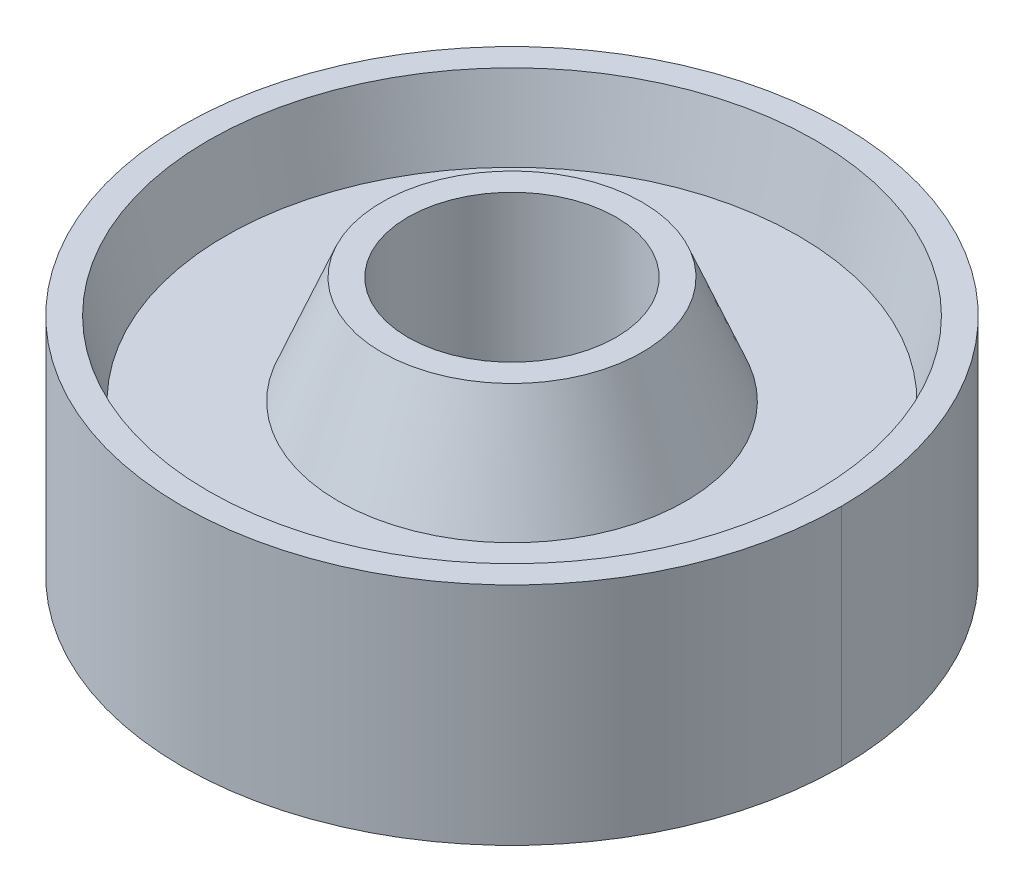
SolidWorks part; units mm, degrees
material "1.6657 (14NiCrMo13-4)"
ref_plane "Alzado" through (0, 0, 0) normal (0, 0, 1) x (1, 0, 0)
ref_plane "Planta" through (0, 0, 0) normal (0, 1, 0) x (1, 0, 0)
ref_plane "Vista lateral" through (0, 0, 0) normal (1, 0, 0) x (0, 0, -1)
sketch "Croquis1" plane through (0, 0, 0) normal (0, 0, 1) x (1, 0, 0)
  line L0 (7.7309, 46.3143) -> (7.7309, 12.6287)
  line L1 (7.7309, 46.3143) -> (22.7309, 46.3143)
  line L2 (22.7309, 46.3143) -> (27.7309, 33.9537)
  line L3 (27.7309, 33.9537) -> (40.7309, 33.9537)
  line L4 (40.7309, 33.9537) -> (42.7309, 42.4715)
  line L5 (42.7309, 42.4715) -> (45.7309, 42.4715)
  line L7 (45.7309, 16.4715) -> (45.7309, 42.4715)
  line L8 (7.7309, 12.6287) -> (22.7309, 12.6287)
  line L9 (22.7309, 12.6287) -> (27.7309, 24.9893)
  line L10 (27.7309, 24.9893) -> (40.7309, 24.9893)
  line L11 (40.7309, 24.9893) -> (42.7309, 16.4715)
  line L12 (7.7309, 46.3143) -> (7.7309, 32.6772) construction
  line L13 (42.7309, 16.4715) -> (45.7309, 16.4715)
  dimension "D2" = 33
  dimension "D3" = 35
  dimension "D4" = 15
  dimension "D5" = 38
  dimension "D6" = 20
revolve "Revolución1" add sketch "Croquis1" angle 360 about L12
sketch "Croquis2" plane through (0, 46.3143, 0) normal (0, 1, 0) x (1, 0, 0)
  circle A0 centre (7.7309, 0) radius 12
extrude "Cortar-Extruir1" cut sketch "Croquis2" against normal up to body
split line "Split Line1"
